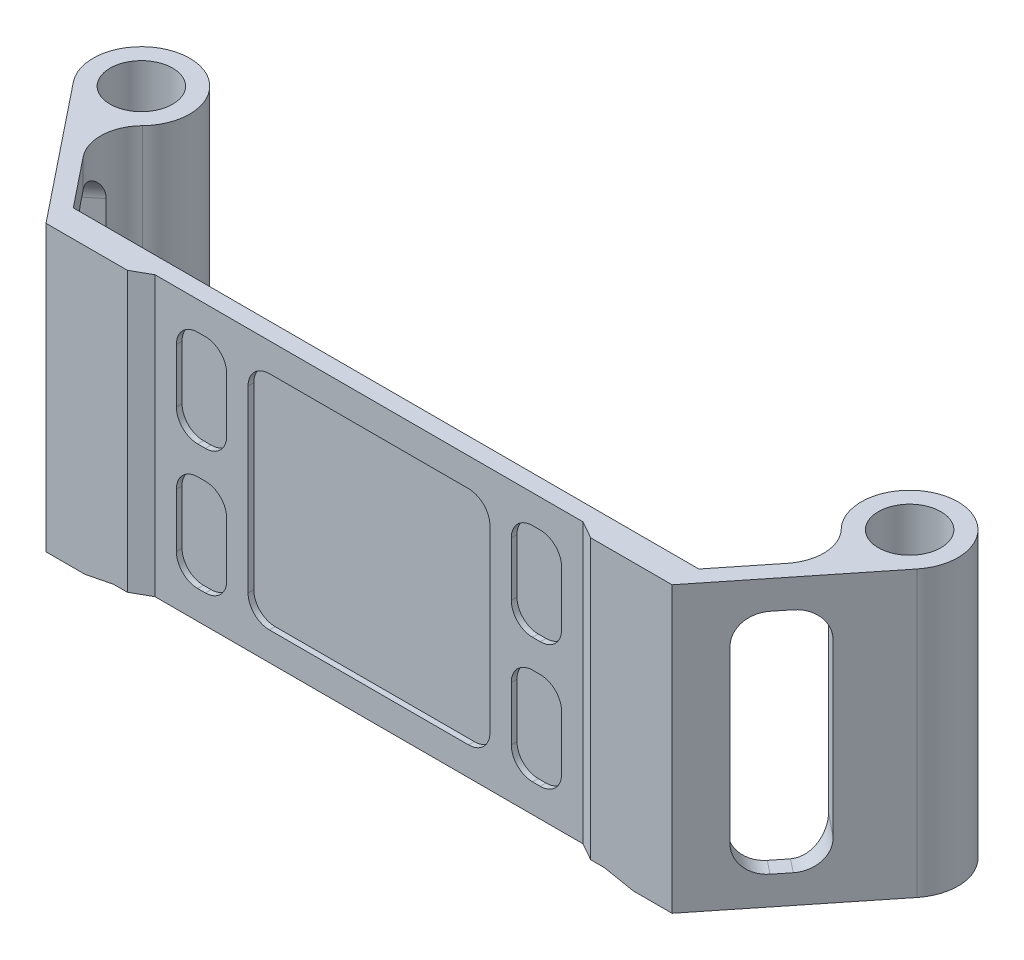
SolidWorks part; units mm, degrees
material "ABS"
ref_plane "前视基准面" through (0, 0, 0) normal (0, 0, 1) x (1, 0, 0)
ref_plane "上视基准面" through (0, 0, 0) normal (0, 1, 0) x (1, 0, 0)
ref_plane "右视基准面" through (0, 0, 0) normal (1, 0, 0) x (0, 0, -1)
sketch "草图1" plane through (0, 0, 0) normal (0, 1, 0) x (1, 0, 0)
  line L0 (0, 29.131) -> (0, -26.0966) construction
  line L1 (-29.6563, -2.1223) -> (-22.5632, -11)
  line L2 (-22.5632, -11) -> (22.5632, -11)
  line L3 (-27.1006, -3.3985) -> (-21.986, -9.8)
  line L4 (-21.986, -9.8) -> (21.986, -9.8)
  line L5 (27.1006, -3.3985) -> (21.986, -9.8)
  line L6 (29.6563, -2.1223) -> (22.5632, -11)
  circle A0 centre (-27, 0) radius 2.2
  arc A1 (-29.6563, -2.1223) -> (-27.1006, -3.3985) centre (-27, 0) cw
  arc A2 (29.6563, -2.1223) -> (27.1006, -3.3985) centre (27, 0) ccw
  circle A3 centre (27, 0) radius 2.2
  point P20 (0, -9.8)
  point P21 (0, -11)
  dimension "D1" = 4.4
  dimension "D2" = 54
  dimension "D3" = 1.2
  dimension "D6" = 1.2
  dimension "D4" = 1.2
  dimension "D5" = 11
extrude "凸台-拉伸1" add sketch "草图1" along normal blind 20
fillet "圆角1" radius 3 2 edges at (27.1006, 10, 3.3985) (-27.1006, 10, 3.3985)
sketch "草图3" plane through (19.1361, 0, 15.2893) normal (0.7813, 0, 0.6242) x (0.6242, 0, -0.7813)
  line L0 (5.4903, 20) -> (16.8536, 20) construction
  line L1 (7.4903, 18) -> (12.6536, 18)
  line L2 (7.4903, 18) -> (7.4903, 1.9964)
  line L3 (7.4903, 1.9964) -> (12.6536, 1.9964)
  line L4 (12.6536, 18) -> (12.6536, 1.9964)
  line L5 (7.4903, 18) -> (12.6536, 1.9964) construction
  line L6 (7.4903, 1.9964) -> (12.6536, 18) construction
  line L7 (5.4903, 0) -> (16.8536, 0) construction
  line L8 (5.4903, 20) -> (5.4903, 0) construction
  point P0 (10.0719, 9.9982)
  dimension "D1" = 2
  dimension "D2" = 1.9964
  dimension "D3" = 2
  dimension "D4" = 2
extrude "切除-拉伸2" cut sketch "草图3" against normal through all
mirror "镜向1" about plane through (0, 0, 0) normal (1, 0, 0) of "切除-拉伸2"
fillet "圆角2" radius 2 8 edges at (-23.3429, 1.9964, 9.063) (-23.3429, 18, 9.063) (-26.2113, 18, 4.7458) (-26.2113, 1.9964, 4.7458) (23.3429, 18, 9.063) (23.3429, 1.9964, 9.063) (26.2113, 18, 4.7458) (26.2113, 1.9964, 4.7458)
sketch "草图4" plane through (0, 20, 0) normal (0, 1, 0) x (1, 0, 0)
  line L0 (-22.5632, -11) -> (-22.0039, -11.7)
  line L1 (-22.0039, -11.7) -> (-16.2842, -11.7)
  line L2 (-16.2842, -11.7) -> (-15.0404, -11)
  line L3 (-22.5632, -11) -> (22.5632, -11) construction
  line L4 (-29.6563, -2.1223) -> (-22.5632, -11) construction
  line L5 (-15.0404, -11) -> (-22.5632, -11)
  line L6 (0, 35.0184) -> (0, -45.6811) construction
  line L7 (15.0404, -11) -> (22.5632, -11)
  line L8 (16.2842, -11.7) -> (15.0404, -11)
  line L9 (22.0039, -11.7) -> (16.2842, -11.7)
  line L10 (22.5632, -11) -> (22.0039, -11.7)
  dimension "D1" = 0.7
extrude "凸台-拉伸2" add sketch "草图4" against normal up to surface (20 mm away) up to face at (-27, 0, 2.2)
sketch "草图2" plane through (0, 0, 11) normal (0, 0, 1) x (1, 0, 0)
  line L0 (-19.2732, 0) -> (-17.2479, 0.4)
  line L1 (-15.0404, 0) -> (15.0404, 0) construction
  line L2 (-17.2479, 0.4) -> (17.2479, 0.4)
  line L3 (0, 0) -> (0, 20) construction
  line L4 (-15.0404, 20) -> (15.0404, 20) construction
  line L5 (19.2732, 0) -> (17.2479, 0.4)
  line L6 (-19.2732, 0) -> (19.2732, 0)
  point P10 (0, 0.4)
  dimension "D1" = 0.4
extrude "切除-拉伸1" cut sketch "草图2" against normal through all both and the other way through all
sketch "草图5" plane through (0, 0, 11) normal (0, 0, 1) x (1, 0, 0)
  line L0 (-15.0404, 0.4) -> (-15.0404, 20) construction
  line L1 (-8.5, 18) -> (8.5, 18)
  line L2 (-8.5, 18) -> (-8.5, 2.4)
  line L3 (-8.5, 2.4) -> (8.5, 2.4)
  line L4 (8.5, 18) -> (8.5, 2.4)
  line L5 (-8.5, 18) -> (8.5, 2.4) construction
  line L6 (-8.5, 2.4) -> (8.5, 18) construction
  line L7 (-13.5404, 18) -> (-10, 18)
  line L8 (-13.5404, 18) -> (-13.5404, 11.2)
  line L9 (-13.5404, 11.2) -> (-10, 11.2)
  line L10 (-10, 18) -> (-10, 11.2)
  line L11 (-13.5404, 18) -> (-10, 11.2) construction
  line L12 (-13.5404, 11.2) -> (-10, 18) construction
  line L13 (-15.0404, 0.4) -> (15.0404, 0.4) construction
  line L14 (-15.0404, 20) -> (15.0404, 20) construction
  line L15 (0, 20) -> (0, 0) construction
  line L16 (13.5404, 11.2) -> (10, 11.2)
  line L17 (10, 18) -> (10, 11.2)
  line L18 (13.5404, 18) -> (10, 18)
  line L19 (13.5404, 18) -> (13.5404, 11.2)
  line L20 (-15.0404, 10.2) -> (15.0404, 10.2) construction
  line L21 (15.0404, 0.4) -> (15.0404, 20) construction
  line L22 (-13.5404, 9.2) -> (-10, 9.2)
  line L23 (-10, 2.4) -> (-10, 9.2)
  line L24 (-13.5404, 2.4) -> (-10, 2.4)
  line L25 (-13.5404, 2.4) -> (-13.5404, 9.2)
  line L26 (13.5404, 2.4) -> (13.5404, 9.2)
  line L27 (13.5404, 2.4) -> (10, 2.4)
  line L28 (10, 2.4) -> (10, 9.2)
  line L29 (13.5404, 9.2) -> (10, 9.2)
  point P0 (0, 10.2)
  point P5 (-11.7702, 14.6)
  dimension "D1" = 1.5
  dimension "D2" = 1.5
  dimension "D3" = 2
  dimension "D4" = 2
  dimension "D5" = 17
  dimension "D6" = 1
extrude "切除-拉伸3" cut sketch "草图5" against normal blind 0.4
fillet "圆角3" radius 1.5 20 edges at (-8.5, 18, 10.8) (-8.5, 2.4, 10.8) (8.5, 2.4, 10.8) (-13.5404, 18, 10.8) (-13.5404, 11.2, 10.8) (-10, 11.2, 10.8) (-10, 18, 10.8) (10, 18, 10.8) (10, 11.2, 10.8) (13.5404, 11.2, 10.8) (13.5404, 18, 10.8) (8.5, 18, 10.8) (-10, 2.4, 10.8) (-10, 9.2, 10.8) (-13.5404, 9.2, 10.8) (13.5404, 9.2, 10.8) (10, 9.2, 10.8) (10, 2.4, 10.8) (13.5404, 2.4, 10.8) (-13.5404, 2.4, 10.8)
